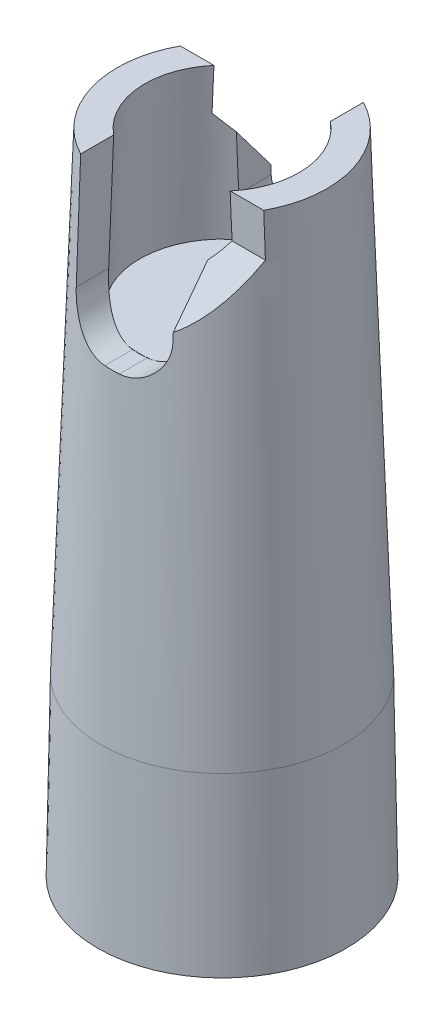
SolidWorks part; units mm, degrees
ref_plane "Front Plane" through (0, 0, 0) normal (0, 0, 1) x (1, 0, 0)
ref_plane "Top Plane" through (0, 0, 0) normal (0, 1, 0) x (1, 0, 0)
ref_plane "Right Plane" through (0, 0, 0) normal (1, 0, 0) x (0, 0, -1)
sketch "Sketch1" plane through (0, 0, 0) normal (0, 1, 0) x (1, 0, 0)
  circle A0 centre (0, 0) radius 2.9972
  dimension "D1" = 5.9944
extrude "insert" add sketch "Sketch1" along normal blind 11.684 draft 2 and the other way blind 4.318 draft 1
ref_plane "top of valve" through (0, 0, 0) normal (0, -1, 0) x (-1, 0, 0)
sketch "Sketch2" plane through (0, 0, 0) normal (0, -1, 0) x (1, 0, 0)
  circle A0 centre (0, 0) radius 2.3114
  dimension "D1" = 4.6228
extrude "insert bore" cut sketch "Sketch2" against normal through all draft 2 and the other way through all
sketch "Sketch3" plane through (0, 0, 0) normal (0, 0, 1) x (1, 0, 0)
  line L0 (0, 0) -> (0, 11.684) construction
  line L1 (1.9034, 11.684) -> (-1.9034, 11.684) construction
  line L2 (2.5892, 11.684) -> (-2.5892, 11.684) construction
  line L3 (-1.1938, 11.684) -> (1.1938, 11.684)
  line L4 (-1.1938, 11.684) -> (-1.1938, 8.89)
  line L5 (-0.1778, 7.874) -> (0.1778, 7.874)
  line L6 (1.1938, 11.684) -> (1.1938, 8.89)
  arc A0 (-0.1778, 7.874) -> (-1.1938, 8.89) centre (-0.1778, 8.89) cw
  arc A1 (1.1938, 8.89) -> (0.1778, 7.874) centre (0.1778, 8.89) cw
  dimension "D3" = 1.016
  dimension "D1" = 3.81
  dimension "D2" = 2.3876
extrude "pass cut" cut sketch "Sketch3" against normal through all and the other way through all
sketch "Sketch4" plane through (0, 0, 0) normal (1, 0, 0) x (0, 0, -1)
  line L0 (1.2424, 11.684) -> (2.7072, 11.684)
  line L1 (2.2975, 11.684) -> (-2.2975, 11.684) construction
  line L2 (2.7072, 11.684) -> (2.7072, 8.7031)
  line L3 (2.7072, 8.7031) -> (1.2424, 10.6387)
  line L4 (1.2424, 10.6387) -> (1.2424, 11.684)
extrude "pass chip" cut sketch "Sketch4" against normal through all
pattern_circular "CirPattern1" count 2 over 360 about axis through (0, -4.318, 0) along (0, 1, 0) of "pass chip"
ref_plane "Plane1" through (0, 7.874, 0) normal (0, -1, 0) x (-1, 0, 0)
sketch "Sketch5" plane through (0, 7.874, 0) normal (0, -1, 0) x (-1, 0, 0)
  circle A0 centre (0, 0) radius 2.032
  dimension "D1" = 4.064
extrude "Boss-Extrude1" add sketch "Sketch5" along normal blind 1.0922
